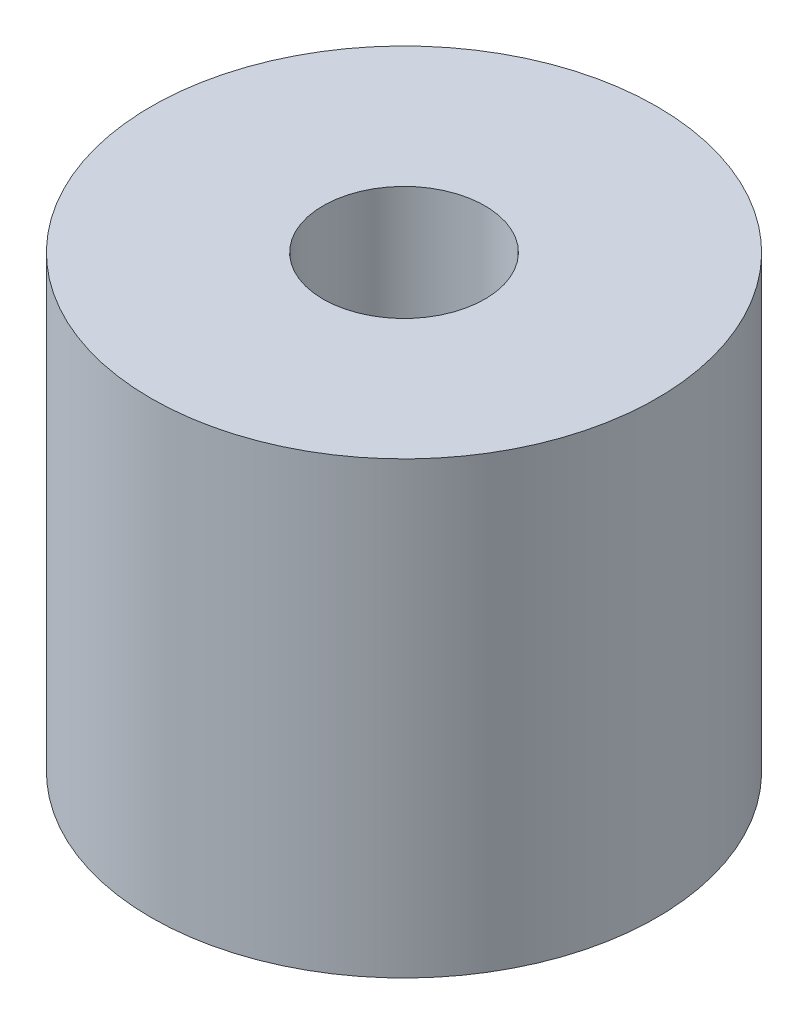
SolidWorks part; units mm, degrees
ref_plane "Front Plane" through (0, 0, 0) normal (0, 0, 1) x (1, 0, 0)
ref_plane "Top Plane" through (0, 0, 0) normal (0, 1, 0) x (1, 0, 0)
ref_plane "Right Plane" through (0, 0, 0) normal (1, 0, 0) x (0, 0, -1)
sketch "Sketch1" plane through (0, 0, 0) normal (0, 1, 0) x (1, 0, 0)
  circle A0 centre (0, 0) radius 7.1437
  circle A1 centre (0, 0) radius 2.286
  dimension "D1" = 14.2875
  dimension "D2" = 4.572
extrude "Boss-Extrude1" add sketch "Sketch1" along normal blind 12.7
